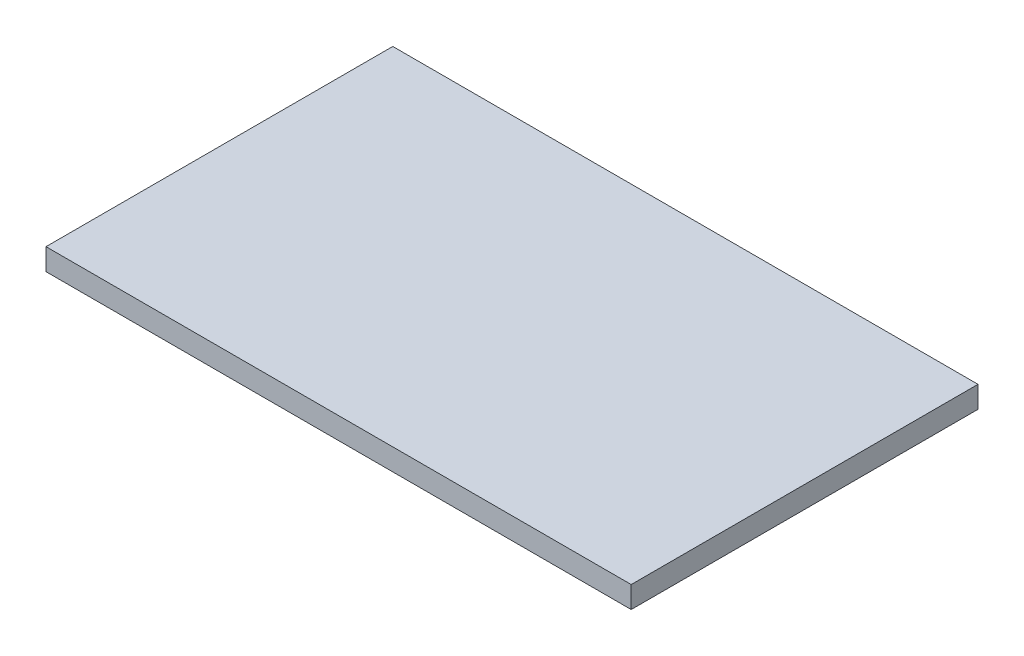
SolidWorks part; units mm, degrees
ref_plane "前视基准面" through (0, 0, 0) normal (0, 0, 1) x (1, 0, 0)
ref_plane "上视基准面" through (0, 0, 0) normal (0, 1, 0) x (1, 0, 0)
ref_plane "右视基准面" through (0, 0, 0) normal (1, 0, 0) x (0, 0, -1)
sketch "草图1" plane through (0, 0, 0) normal (0, 0, 1) x (1, 0, 0)
  line L1 (-135, -5) -> (135, -5)
  line L2 (-135, -5) -> (-135, 5)
  line L3 (-135, 5) -> (135, 5)
  line L4 (135, -5) -> (135, 5)
  line L5 (-135, -5) -> (135, 5) construction
  line L6 (-135, 5) -> (135, -5) construction
  point P0 (0, 0)
  dimension "D1" = 10
  dimension "D2" = 270
extrude "凸台-拉伸1" add sketch "草图1" along normal blind 160
